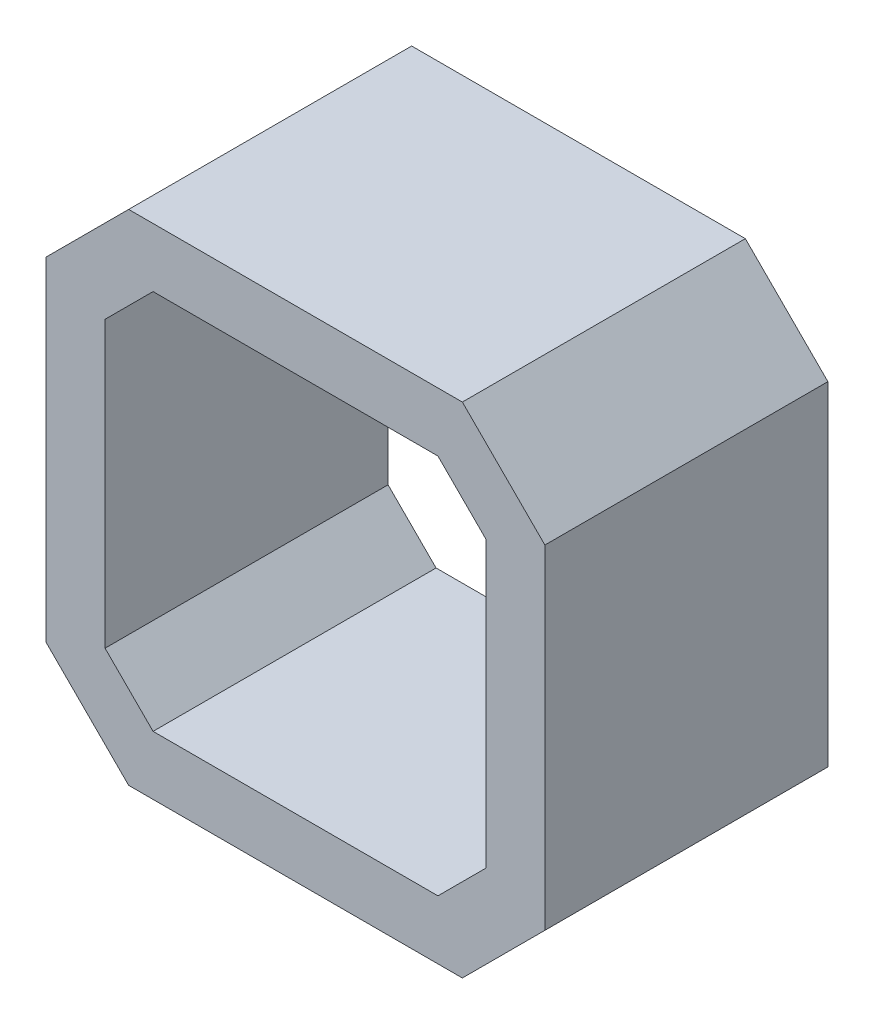
SolidWorks part; units mm, degrees
ref_plane "Plan de face" through (0, 0, 0) normal (0, 0, 1) x (1, 0, 0)
ref_plane "Plan de dessus" through (0, 0, 0) normal (0, 1, 0) x (1, 0, 0)
ref_plane "Plan de droite" through (0, 0, 0) normal (1, 0, 0) x (0, 0, -1)
sketch "Esquisse1" plane through (0, 0, 0) normal (0, 0, 1) x (1, 0, 0)
  line L0 (14.15, 21.15) -> (21.15, 14.15)
  line L1 (-14.15, 21.15) -> (14.15, 21.15)
  line L2 (-21.15, 14.15) -> (-21.15, -14.15)
  line L3 (-14.15, -21.15) -> (14.15, -21.15)
  line L4 (21.15, 14.15) -> (21.15, -14.15)
  line L5 (-21.15, 21.15) -> (21.15, -21.15) construction
  line L6 (-21.15, -21.15) -> (21.15, 21.15) construction
  line L7 (21.15, -14.15) -> (14.15, -21.15)
  line L8 (-21.15, -14.15) -> (-14.15, -21.15)
  line L9 (-14.15, 21.15) -> (-21.15, 14.15)
  line L10 (-12.0789, 16.15) -> (12.0789, 16.15)
  line L11 (12.0789, 16.15) -> (16.15, 12.0789)
  line L12 (16.15, 12.0789) -> (16.15, -12.0789)
  line L13 (16.15, -12.0789) -> (12.0789, -16.15)
  line L14 (-12.0789, -16.15) -> (12.0789, -16.15)
  line L15 (-16.15, -12.0789) -> (-12.0789, -16.15)
  line L16 (-16.15, 12.0789) -> (-16.15, -12.0789)
  line L17 (-12.0789, 16.15) -> (-16.15, 12.0789)
  point P0 (0, 0)
  dimension "D1" = 42.3
  dimension "D2" = 5
extrude "Boss.-Extru.1" add sketch "Esquisse1" along normal blind 24
